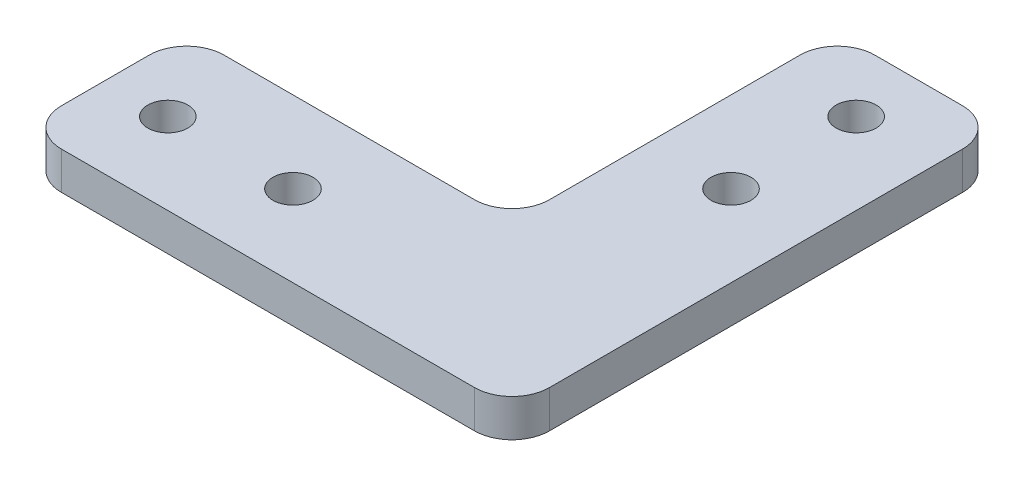
SolidWorks part; units mm, degrees
material "Thornel Mat VMA"
ref_plane "前视基准面" through (0, 0, 0) normal (0, 0, 1) x (1, 0, 0)
ref_plane "上视基准面" through (0, 0, 0) normal (0, 1, 0) x (1, 0, 0)
ref_plane "右视基准面" through (0, 0, 0) normal (1, 0, 0) x (0, 0, -1)
other "Configuration Table"
sketch "草图1" plane through (0, 0, 0) normal (0, 1, 0) x (1, 0, 0)
  line L0 (-55.7986, 6.5) -> (7.4388, 6.5) construction
  line L1 (0, 0) -> (-39, 0)
  line L2 (0, 0) -> (0, 13)
  line L3 (0, 13) -> (-39, 13) construction
  line L4 (-39, 0) -> (-39, 13)
  line L5 (0, 0) -> (-13, 0)
  line L6 (0, 0) -> (0, 39)
  line L7 (0, 39) -> (-13, 39)
  line L8 (-13, 0) -> (-13, 39) construction
  line L9 (-6.5, 47.9568) -> (-6.5, -5.8619) construction
  line L10 (-39, 13) -> (-13, 13)
  line L11 (-13, 13) -> (-13, 39)
  circle A0 centre (-24, 6.5) radius 1.6
  circle A1 centre (-34, 6.5) radius 1.6
  circle A2 centre (-6.5, 24) radius 1.6
  circle A3 centre (-6.5, 34) radius 1.6
  dimension "D5" = 3.2
  dimension "D6" = 11
  dimension "D7" = 10
  dimension "D9" = 11
  dimension "D10" = 10
  dimension "D1" = 13
  dimension "D2" = 13
  dimension "D3" = 6.5
  dimension "D4" = 6.5
  dimension "D8" = 5
  dimension "D11" = 5
extrude "凸台-拉伸1" add sketch "草图1" along normal blind 3 contours L11 L10 L4 L1 L2 L6 L7 A3 A2 A1 A0
fillet "圆角1" radius 3 6 edges at (0, 1.5, 0) (-13, 1.5, -39) (-39, 1.5, 0) (-39, 1.5, -13) (-13, 1.5, -13) (0, 1.5, -39)
